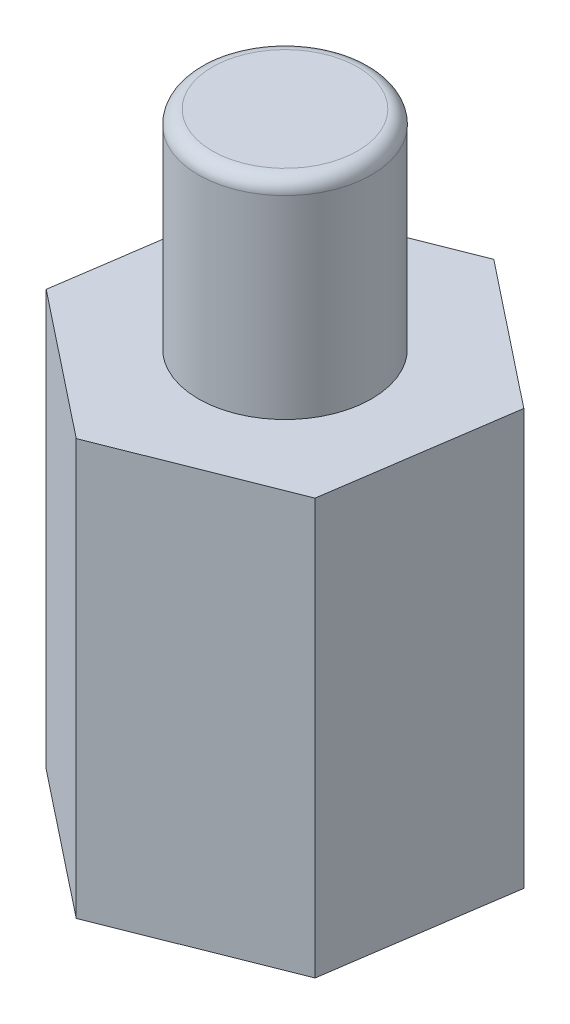
SolidWorks part; units mm, degrees
ref_plane "Alzado" through (0, 0, 0) normal (0, 0, 1) x (1, 0, 0)
ref_plane "Planta" through (0, 0, 0) normal (0, 1, 0) x (1, 0, 0)
ref_plane "Vista lateral" through (0, 0, 0) normal (1, 0, 0) x (0, 0, -1)
sketch "Croquis base" plane through (0, 0, 0) normal (0, 1, 0) x (1, 0, 0)
  line L1 (2.0823, -1.6485) -> (2.4688, 0.9791)
  line L2 (2.4688, 0.9791) -> (0.3865, 2.6275)
  line L3 (0.3865, 2.6275) -> (-2.0823, 1.6485)
  line L4 (-2.0823, 1.6485) -> (-2.4688, -0.9791)
  line L5 (-2.4688, -0.9791) -> (-0.3865, -2.6275)
  line L6 (-0.3865, -2.6275) -> (2.0823, -1.6485)
  circle A0 centre (0, 0) radius 2.3 construction
extrude "Saliente-Extruir1" add sketch "Croquis base" along normal blind 6
sketch "Croquis cara" plane through (0, 6, 0) normal (0, 1, 0) x (1, 0, 0)
  circle A0 centre (0, 0) radius 1.25
  dimension "D1" = 2.5
extrude "Saliente-Extruir2" add sketch "Croquis cara" along normal blind 3
fillet "Redondeo1" radius 0.2 1 edges at (0, 9, 1.25)
sketch "Croquis1" plane through (0, 0, 0) normal (0, -1, 0) x (1, 0, 0)
  circle A0 centre (0, 0) radius 1.25
extrude "Cortar-Extruir1" cut sketch "Croquis1" against normal blind 3
